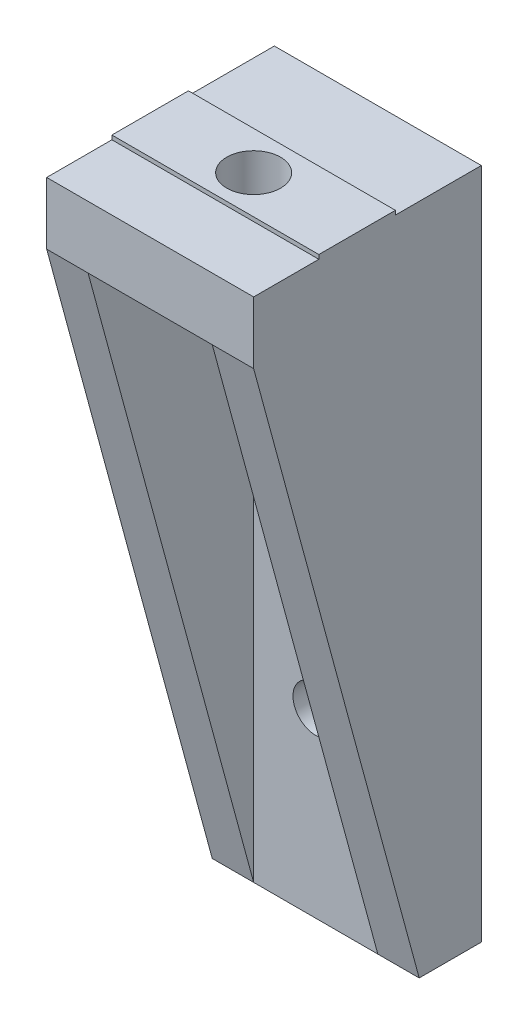
SolidWorks part; units mm, degrees
ref_plane "Спереди" through (0, 0, 0) normal (0, 0, 1) x (1, 0, 0)
ref_plane "Сверху" through (0, 0, 0) normal (0, 1, 0) x (1, 0, 0)
ref_plane "Справа" through (0, 0, 0) normal (1, 0, 0) x (0, 0, -1)
sketch "Эскиз3" plane through (0, 0, 0) normal (0, 0, 1) x (1, 0, 0)
  line L1 (10, 0) -> (10, 59)
  line L2 (10, 59) -> (-10, 59)
  line L3 (-10, 59) -> (-10, 0)
  line L4 (10, 0) -> (-10, 0)
  point P5 (0, 0)
  dimension "D2" = 59
  dimension "D1" = 20
extrude "Бобышка-Вытянуть2" add sketch "Эскиз3" along normal blind 6 separate body
sketch "Эскиз10" plane through (0, 0, 0) normal (0, 0, -1) x (-1, 0, 0)
  line L0 (-10, 0) -> (-10, 59) construction
  line L5 (10, 0) -> (-10, 0) construction
  circle A2 centre (0, 17.5) radius 2.2
  dimension "D3" = 4.4
  dimension "D6" = 10
  dimension "D9" = 17.5
extrude "Вырез-Вытянуть3" cut sketch "Эскиз10" against normal through all
sketch "Эскиз11" plane through (0, 59, 0) normal (0, 1, 0) x (1, 0, 0)
  line L1 (-10, 0) -> (10, 0)
  line L2 (-10, 0) -> (-10, -22)
  line L3 (-10, -22) -> (10, -22)
  line L4 (10, 0) -> (10, -22)
  dimension "D1" = 22
extrude "Бобышка-Вытянуть5" add sketch "Эскиз11" along normal blind 6
sketch "Эскиз9" plane through (0, 65, -43.4) normal (0, -1, 0) x (1, 0, 0)
  line L0 (-10, 65.4) -> (10, 65.4) construction
  line L1 (-10, 59.1) -> (10, 59.1)
  line L2 (-10, 59.1) -> (-10, 51.7)
  line L3 (-10, 51.7) -> (10, 51.7)
  line L4 (10, 59.1) -> (10, 51.7)
  line L7 (-10, 43.4) -> (-10, 65.4) construction
  line L8 (10, 65.4) -> (10, 43.4) construction
  point P10 (-10, 55.4)
  dimension "D1" = 7.4
  dimension "D2" = 10
extrude "Бобышка-Вытянуть4" add sketch "Эскиз9" against normal blind 0.4
sketch "Эскиз13" plane through (0, 65.4, 0) normal (0, 1, 0) x (1, 0, 0)
  line L0 (-10, -15.7) -> (-10, -22) construction
  line L1 (-10, -22) -> (10, -22) construction
  circle A0 centre (0, -12) radius 2.6
  dimension "D1" = 5.2
  dimension "D3" = 10
  dimension "D2" = 10
extrude "Вырез-Вытянуть4" cut sketch "Эскиз13" against normal through all
sketch "Эскиз17" plane through (-10, 0, 0) normal (-1, 0, 0) x (0, 0, 1)
  line L0 (22, 59) -> (6, 59)
  line L1 (6, 59) -> (6, 0)
  line L2 (6, 0) -> (22, 59)
extrude "Бобышка-Вытянуть6" add sketch "Эскиз17" against normal blind 4
mirror "Зеркальное отражение1" about plane through (0, 0, 0) normal (1, 0, 0) of "Бобышка-Вытянуть6"
